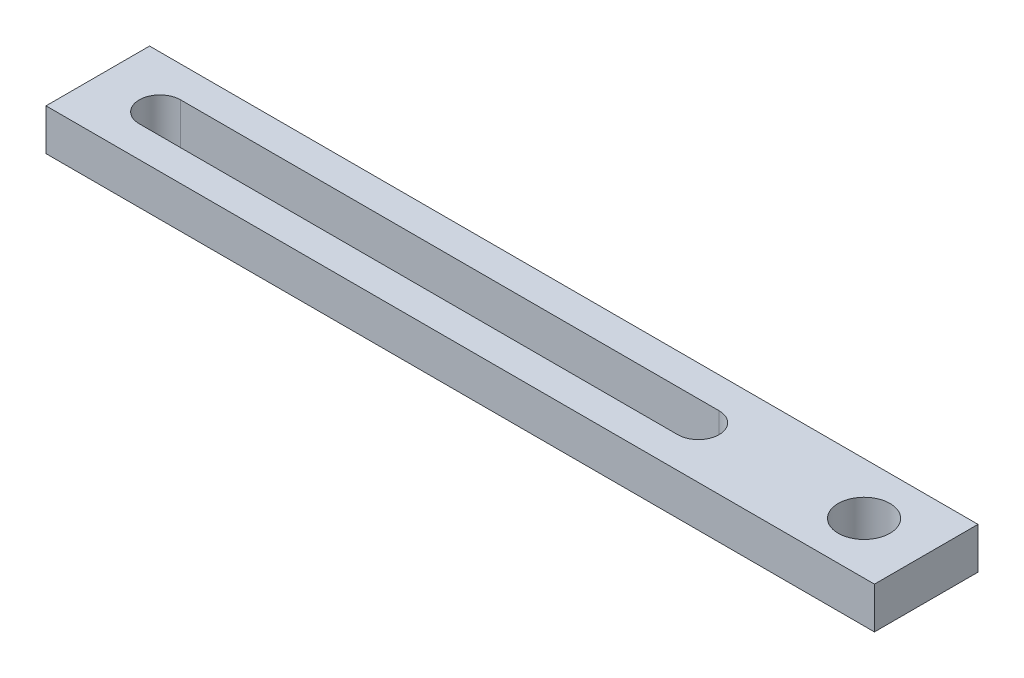
SolidWorks part; units mm, degrees
material "Pine"
ref_plane "Front Plane" through (0, 0, 0) normal (0, 0, 1) x (1, 0, 0)
ref_plane "Top Plane" through (0, 0, 0) normal (0, 1, 0) x (1, 0, 0)
ref_plane "Right Plane" through (0, 0, 0) normal (1, 0, 0) x (0, 0, -1)
other "Configuration Table"
sketch "Sketch1" plane through (0, 0, 0) normal (0, 1, 0) x (1, 0, 0)
  line L0 (-234.95, -15.875) -> (-69.85, -15.875) construction
  line L1 (0, 0) -> (-254, 0)
  line L2 (0, 0) -> (0, -31.75)
  line L3 (0, -31.75) -> (-254, -31.75)
  line L4 (-254, 0) -> (-254, -31.75)
  line L5 (-234.95, -9.525) -> (-69.85, -9.525)
  line L6 (-234.95, -22.225) -> (-69.85, -22.225)
  line L7 (-254, -15.875) -> (57.6439, -15.875) construction
  arc A0 (-234.95, -9.525) -> (-234.95, -22.225) centre (-234.95, -15.875) ccw
  arc A1 (-69.85, -22.225) -> (-69.85, -9.525) centre (-69.85, -15.875) ccw
  circle A2 centre (-19.05, -15.875) radius 7.9375
  point P7 (-152.4, -15.875)
  point P14 (-241.3, -15.875)
  point P15 (-63.5, -15.875)
  dimension "D3" = 15.875
  dimension "D1" = 254
  dimension "D2" = 31.75
  dimension "D4" = 12.7
  dimension "D5" = 177.8
  dimension "D6" = 19.05
  dimension "D7" = 19.05
extrude "Boss-Extrude1" add sketch "Sketch1" along normal blind 12.7
